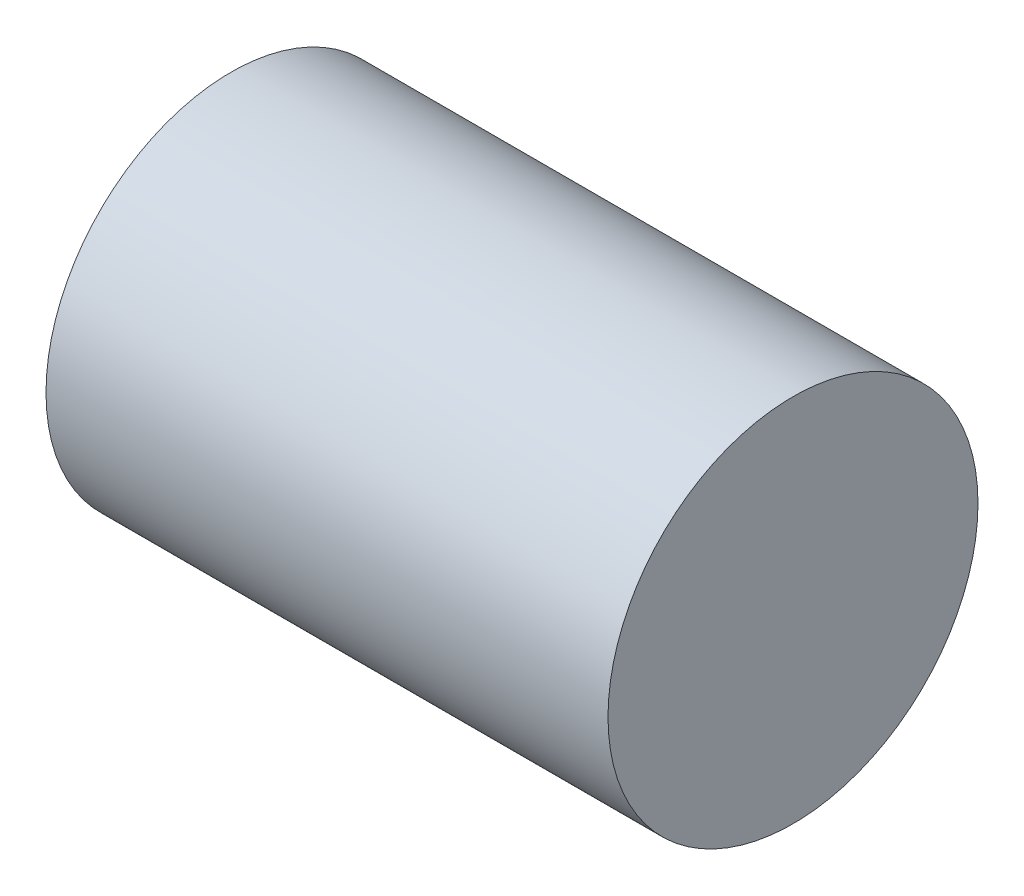
SolidWorks part; units mm, degrees
ref_plane "Front Plane" through (0, 0, 0) normal (0, 0, 1) x (1, 0, 0)
ref_plane "Top Plane" through (0, 0, 0) normal (0, 1, 0) x (1, 0, 0)
ref_plane "Right Plane" through (0, 0, 0) normal (1, 0, 0) x (0, 0, -1)
sketch "Sketch1" plane through (0, 0, 0) normal (0, 1, 0) x (1, 0, 0)
  line L0 (-74.3173, 0) -> (77.7511, 0) construction
  line L1 (-35.687, 0) -> (-35.687, 23.495)
  line L2 (-35.687, 23.495) -> (35.687, 23.495)
  line L3 (35.687, 23.495) -> (35.687, 0)
  line L4 (35.687, 0) -> (-35.687, 0)
  dimension "D1" = 71.374
  dimension "D2" = 35.687
  dimension "D3" = 23.495
revolve "Revolve1" add sketch "Sketch1" angle 360 about L0
